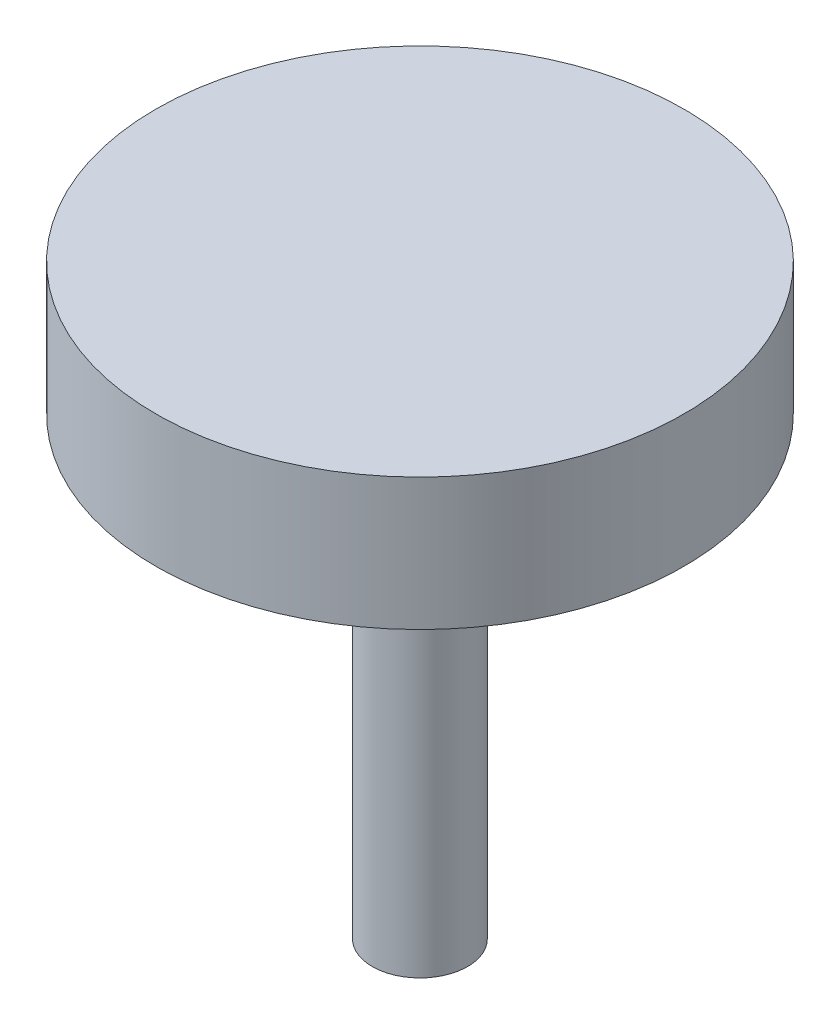
SolidWorks part; units mm, degrees
ref_plane "Front Plane" through (0, 0, 0) normal (0, 0, 1) x (1, 0, 0)
ref_plane "Top Plane" through (0, 0, 0) normal (0, 1, 0) x (1, 0, 0)
ref_plane "Right Plane" through (0, 0, 0) normal (1, 0, 0) x (0, 0, -1)
sketch "Sketch1" plane through (0, 0, 0) normal (0, 0, 1) x (1, 0, 0)
  line L4 (0, 0) -> (0.65, 0)
  line L5 (0.65, 0) -> (0.65, 8)
  line L6 (0.65, 8) -> (0, 8)
  line L7 (0, 8) -> (0, 0)
  dimension "D1" = 8
  dimension "D2" = 0.65
revolve "Revolve1" add sketch "Sketch1" angle 360 about L7
sketch "Sketch2" plane through (0, 0, 0) normal (0, 0, 1) x (1, 0, 0)
  line L0 (0, 8) -> (0, 6.2)
  line L1 (0.65, 8) -> (-0.65, 8) construction
  line L2 (0, 6.2) -> (3.6, 6.2)
  line L3 (3.6, 6.2) -> (3.6, 8)
  line L4 (3.6, 8) -> (0, 8)
  dimension "D1" = 3.6
  dimension "D2" = 1.8
revolve "Revolve2" add sketch "Sketch2" angle 360 about L0
